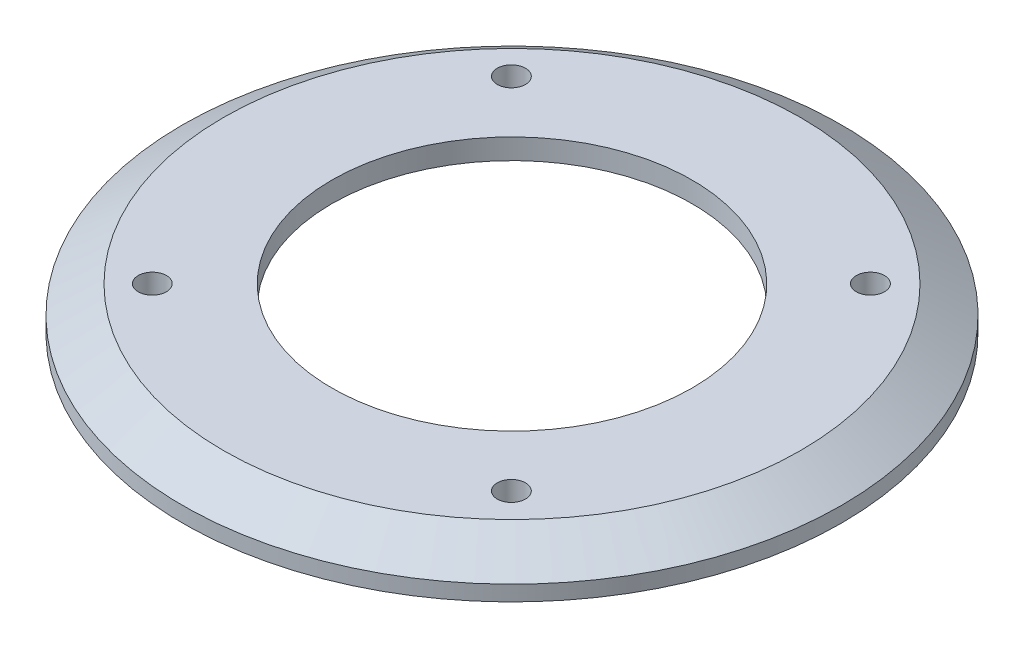
SolidWorks part; units mm, degrees
ref_plane "前视基准面" through (0, 0, 0) normal (0, 0, 1) x (1, 0, 0)
ref_plane "上视基准面" through (0, 0, 0) normal (0, 1, 0) x (1, 0, 0)
ref_plane "右视基准面" through (0, 0, 0) normal (1, 0, 0) x (0, 0, -1)
sketch "草图1" plane through (0, 0, 0) normal (0, 0, 1) x (1, 0, 0)
  line L0 (-14.7227, 34.4113) -> (-14.7227, -138.7342) construction
  line L2 (-84.9727, -8.7887) -> (-127.2227, -8.7887)
  line L3 (-84.9727, 28.2113) -> (-84.9727, -13.7887) construction
  line L4 (-143.2227, -19.2887) -> (-143.2227, -25.2887)
  line L5 (-143.2227, -25.2887) -> (-128.2227, -25.2887)
  line L6 (-128.2227, -25.2887) -> (-128.2227, -16.7887)
  line L7 (-128.2227, -16.7887) -> (-84.9727, -16.7887)
  line L8 (-84.9727, -16.7887) -> (-84.9727, -8.7887)
  line L9 (-127.2227, -8.7887) -> (-143.2227, -19.2887)
  dimension "D1" = 70.25
  dimension "D2" = 15
  dimension "D3" = 8.5
  dimension "D4" = 8
  dimension "D5" = 6
  dimension "D6" = 113.5
  dimension "D7" = 16
revolve "旋转1" add sketch "草图1" angle 360 about L0
sketch "草图2" plane through (0, -16.7887, 0) normal (0, -1, 0) x (1, 0, 0)
  circle A0 centre (-84.9727, 70) radius 5.5
  circle A1 centre (55.0273, 70) radius 5.5
  circle A2 centre (55.0273, -70) radius 5.5
  circle A3 centre (-84.9727, -70) radius 5.5
extrude "切除-拉伸1" cut sketch "草图2" against normal blind 10
